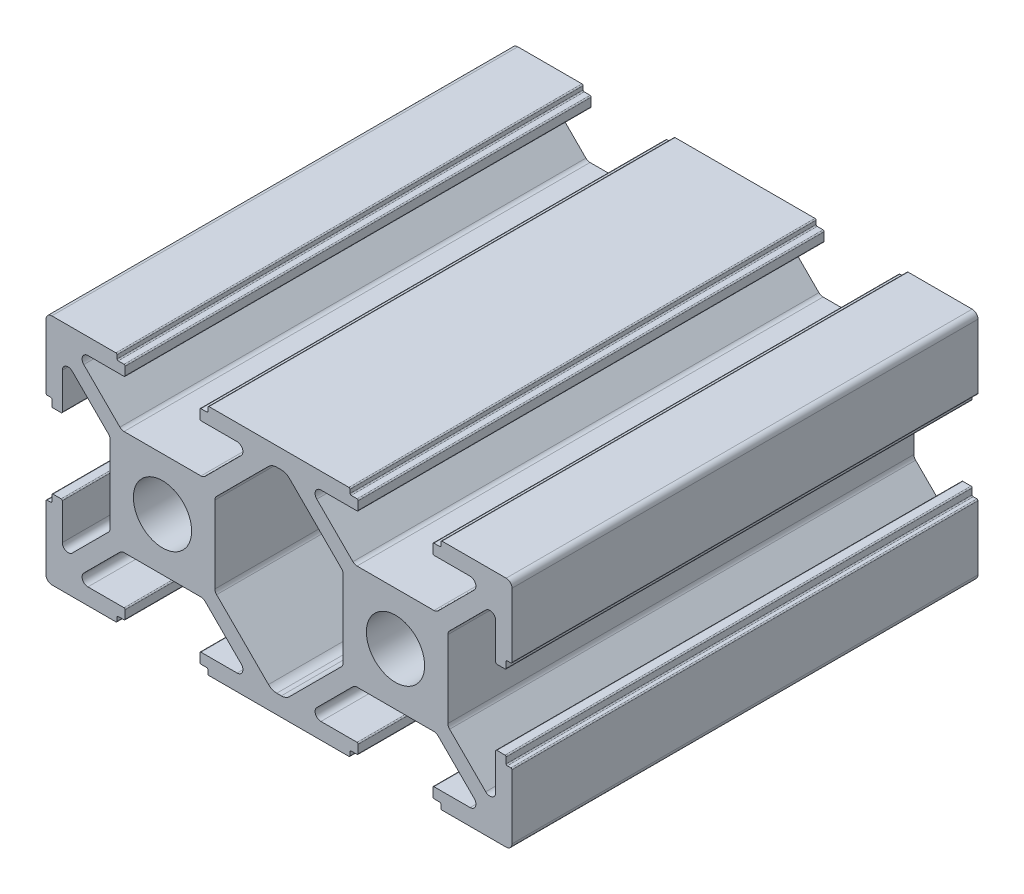
SolidWorks part; units mm, degrees
material "6061 Alaşım"
ref_plane "Ön Düzlem" through (0, 0, 0) normal (0, 0, 1) x (1, 0, 0)
ref_plane "Üst Düzlem" through (0, 0, 0) normal (0, 1, 0) x (1, 0, 0)
ref_plane "Sağ Düzlem" through (0, 0, 0) normal (1, 0, 0) x (0, 0, -1)
sketch "Çizim1" plane through (0, 0, 0) normal (0, 0, 1) x (1, 0, 0)
  line L0 (0, 0) -> (10, 10)
  line L1 (10, -10) -> (-10, -10)
  line L2 (10, -10) -> (10, 10)
  line L3 (10, 10) -> (-10, 10)
  line L4 (-10, -10) -> (-10, 10)
  line L5 (0, 10) -> (0, -10)
  line L6 (10, 0) -> (-10, 0)
  line L7 (4.5, 3.5101) -> (10, 9.0101)
  line L8 (3.5101, 4.5) -> (9.0101, 10)
  line L9 (10, 3.2) -> (8.6, 3.2)
  line L10 (8.6, 3.3) -> (8.6, 6.4029)
  line L11 (6.4029, 8.6) -> (3.3, 8.6)
  line L12 (3.2, 8.6) -> (3.2, 10)
  line L13 (3.6565, 4.6464) -> (6.7565, 7.7464)
  line L14 (7.7464, 6.7565) -> (4.6464, 3.6565)
  line L15 (3.2, 10) -> (9.5, 10)
  line L16 (10, 9.5) -> (10, 3.2)
  line L17 (4.5, 3.3029) -> (4.5, 0)
  line L18 (3.3029, 4.5) -> (0, 4.5)
  line L19 (3.3, 9.5) -> (3.8, 9.5)
  line L20 (3.9, 9.6) -> (3.9, 9.9)
  line L21 (3.2, 9.4) -> (3.2, 8.7)
  line L22 (4, 10) -> (9.5, 10)
  line L23 (9.5, 3.3) -> (9.5, 3.8)
  line L24 (9.6, 3.9) -> (9.9, 3.9)
  line L25 (8.7, 3.2) -> (9.4, 3.2)
  line L26 (10, 4) -> (10, 9.5)
  line L27 (0, 0) -> (10, -10)
  line L28 (3.3029, -4.5) -> (0, -4.5)
  line L29 (6.7565, -7.7464) -> (3.6565, -4.6464)
  line L30 (3.3, -8.6) -> (6.4029, -8.6)
  line L31 (3.2, -8.7) -> (3.2, -9.4)
  line L32 (3.3, -9.5) -> (3.8, -9.5)
  line L33 (3.9, -9.6) -> (3.9, -9.9)
  line L34 (4, -10) -> (9.5, -10)
  line L35 (10, -4) -> (10, -9.5)
  line L36 (9.6, -3.9) -> (9.9, -3.9)
  line L37 (9.5, -3.3) -> (9.5, -3.8)
  line L38 (9.4, -3.2) -> (8.7, -3.2)
  line L39 (8.6, -6.4029) -> (8.6, -3.3)
  line L40 (4.6464, -3.6565) -> (7.7464, -6.7565)
  line L41 (4.5, -3.3029) -> (4.5, 0)
  line L42 (0, 0) -> (-10, -10)
  line L43 (-4.5, -3.3029) -> (-4.5, 0)
  line L44 (-7.7464, -6.7565) -> (-4.6464, -3.6565) construction
  line L45 (-4.6464, 3.6565) -> (-9.0971, 8.1071)
  line L46 (-9.8042, 8.4) -> (-10, 8.4)
  line L47 (-10, -8.4) -> (-9.8042, -8.4)
  line L48 (-9.0971, -8.1071) -> (-4.6464, -3.6565)
  line L49 (-10, -4) -> (-10, -9.5)
  line L50 (-4, -10) -> (-9.5, -10)
  line L51 (-3.9, -9.6) -> (-3.9, -9.9)
  line L52 (-3.3, -9.5) -> (-3.8, -9.5)
  line L53 (-3.2, -9.4) -> (-3.2, -8.7)
  line L54 (-6.4029, -8.6) -> (-3.3, -8.6)
  line L55 (-3.6565, -4.6464) -> (-6.7565, -7.7464)
  line L56 (-3.3029, -4.5) -> (0, -4.5)
  line L57 (0, 0) -> (-10, 10)
  line L58 (-3.3029, 4.5) -> (0, 4.5)
  line L59 (-6.7565, 7.7464) -> (-3.6565, 4.6464)
  line L60 (-3.3, 8.6) -> (-6.4029, 8.6)
  line L61 (-3.2, 8.7) -> (-3.2, 9.4)
  line L62 (-3.3, 9.5) -> (-3.8, 9.5)
  line L63 (-3.9, 9.6) -> (-3.9, 9.9)
  line L64 (-4, 10) -> (-9.5, 10)
  line L65 (-10, 4) -> (-10, 9.5)
  line L70 (-4.6464, 3.6565) -> (-7.7464, 6.7565) construction
  line L71 (-4.5, 3.3029) -> (-4.5, 0)
  line L72 (-9.4, 3.2) -> (-8.7, 3.2) [skipped]
  line L73 (-8.6, 6.4029) -> (-8.6, 3.3) [skipped]
  line L74 (-9.5, 3.3) -> (-9.5, 3.8) [skipped]
  line L75 (-9.6, 3.9) -> (-9.9, 3.9) [skipped]
  line L76 (-8.6, -3.3) -> (-8.6, -6.4029) [skipped]
  line L77 (-9.6, -3.9) -> (-9.9, -3.9) [skipped]
  line L78 (-9.5, -3.3) -> (-9.5, -3.8) [skipped]
  line L79 (-8.7, -3.2) -> (-9.4, -3.2) [skipped]
  circle A0 centre (0, 0) radius 2.5
  arc A1 (10, 9.5) -> (9.5, 10) centre (9.5, 9.5) ccw
  arc A2 (4.5, 3.3029) -> (4.6464, 3.6565) centre (5, 3.3029) cw
  arc A3 (3.6565, 4.6464) -> (3.3029, 4.5) centre (3.3029, 5) cw
  arc A4 (8.6, 6.4029) -> (7.7464, 6.7565) centre (8.1, 6.4029) ccw
  arc A5 (6.4029, 8.6) -> (6.7565, 7.7464) centre (6.4029, 8.1) cw
  arc A6 (9.5, 3.8) -> (9.6, 3.9) centre (9.6, 3.8) cw
  arc A7 (9.9, 3.9) -> (10, 4) centre (9.9, 4) ccw
  arc A8 (8.7, 3.2) -> (8.6, 3.3) centre (8.7, 3.3) cw
  arc A9 (9.5, 3.3) -> (9.4, 3.2) centre (9.4, 3.3) cw
  arc A10 (3.3, 8.6) -> (3.2, 8.7) centre (3.3, 8.7) cw
  arc A11 (3.8, 9.5) -> (3.9, 9.6) centre (3.8, 9.6) ccw
  arc A12 (3.9, 9.9) -> (4, 10) centre (4, 9.9) cw
  arc A13 (3.3, 9.5) -> (3.2, 9.4) centre (3.3, 9.4) ccw
  arc A14 (3.3029, -4.5) -> (3.6565, -4.6464) centre (3.3029, -5) cw
  arc A15 (6.4029, -8.6) -> (6.7565, -7.7464) centre (6.4029, -8.1) ccw
  arc A16 (3.2, -8.7) -> (3.3, -8.6) centre (3.3, -8.7) cw
  arc A17 (3.3, -9.5) -> (3.2, -9.4) centre (3.3, -9.4) cw
  arc A18 (3.8, -9.5) -> (3.9, -9.6) centre (3.8, -9.6) cw
  arc A19 (3.9, -9.9) -> (4, -10) centre (4, -9.9) ccw
  arc A20 (9.5, -10) -> (10, -9.5) centre (9.5, -9.5) ccw
  arc A21 (9.9, -3.9) -> (10, -4) centre (9.9, -4) cw
  arc A22 (9.5, -3.8) -> (9.6, -3.9) centre (9.6, -3.8) ccw
  arc A23 (9.5, -3.3) -> (9.4, -3.2) centre (9.4, -3.3) ccw
  arc A24 (8.6, -3.3) -> (8.7, -3.2) centre (8.7, -3.3) cw
  arc A25 (8.6, -6.4029) -> (7.7464, -6.7565) centre (8.1, -6.4029) cw
  arc A26 (4.6464, -3.6565) -> (4.5, -3.3029) centre (5, -3.3029) cw
  arc A27 (-4.5, -3.3029) -> (-4.6464, -3.6565) centre (-5, -3.3029) cw
  arc A28 (-9.0971, 8.1071) -> (-9.8042, 8.4) centre (-9.8042, 7.4) ccw
  arc A29 (-9.8042, -8.4) -> (-9.0971, -8.1071) centre (-9.8042, -7.4) ccw
  arc A34 (-3.9, -9.9) -> (-4, -10) centre (-4, -9.9) cw
  arc A35 (-3.8, -9.5) -> (-3.9, -9.6) centre (-3.8, -9.6) ccw
  arc A36 (-3.3, -9.5) -> (-3.2, -9.4) centre (-3.3, -9.4) ccw
  arc A37 (-3.3, -8.6) -> (-3.2, -8.7) centre (-3.3, -8.7) cw
  arc A38 (-6.4029, -8.6) -> (-6.7565, -7.7464) centre (-6.4029, -8.1) cw
  arc A39 (-3.6565, -4.6464) -> (-3.3029, -4.5) centre (-3.3029, -5) cw
  arc A40 (-3.3029, 4.5) -> (-3.6565, 4.6464) centre (-3.3029, 5) cw
  arc A41 (-6.4029, 8.6) -> (-6.7565, 7.7464) centre (-6.4029, 8.1) ccw
  arc A42 (-3.2, 8.7) -> (-3.3, 8.6) centre (-3.3, 8.7) cw
  arc A43 (-3.3, 9.5) -> (-3.2, 9.4) centre (-3.3, 9.4) cw
  arc A44 (-3.8, 9.5) -> (-3.9, 9.6) centre (-3.8, 9.6) cw
  arc A45 (-3.9, 9.9) -> (-4, 10) centre (-4, 9.9) ccw
  arc A52 (-4.6464, 3.6565) -> (-4.5, 3.3029) centre (-5, 3.3029) cw
  arc A53 (-10, -9.5) -> (-9.5, -10) centre (-9.5, -9.5) ccw construction
  arc A54 (-9.5, 10) -> (-10, 9.5) centre (-9.5, 9.5) ccw construction
  arc A55 (-8.6, 3.3) -> (-8.7, 3.2) centre (-8.7, 3.3) cw [skipped]
  arc A56 (-9.5, 3.8) -> (-9.6, 3.9) centre (-9.6, 3.8) ccw [skipped]
  arc A57 (-9.9, 3.9) -> (-10, 4) centre (-9.9, 4) cw [skipped]
  arc A58 (-9.5, 3.3) -> (-9.4, 3.2) centre (-9.4, 3.3) ccw [skipped]
  arc A59 (-8.6, -6.4029) -> (-7.7464, -6.7565) centre (-8.1, -6.4029) ccw [skipped]
  arc A60 (-9.9, -3.9) -> (-10, -4) centre (-9.9, -4) ccw [skipped]
  arc A61 (-9.5, -3.8) -> (-9.6, -3.9) centre (-9.6, -3.8) cw [skipped]
  arc A62 (-9.5, -3.3) -> (-9.4, -3.2) centre (-9.4, -3.3) cw [skipped]
  arc A63 (-8.7, -3.2) -> (-8.6, -3.3) centre (-8.7, -3.3) cw [skipped]
  arc A64 (-8.6, 6.4029) -> (-7.7464, 6.7565) centre (-8.1, 6.4029) cw [skipped]
  point P0 (0, 0)
  point P32 (8.6, 7.6101)
  point P35 (7.6101, 8.6)
  point P41 (9.5, 3.9)
  point P44 (10, 3.9)
  point P50 (9.5, 3.2)
  point P62 (3.9, 9.5)
  point P65 (3.9, 10)
  point P68 (3.2, 9.5)
  point P198 (0, 0)
  dimension "D3" = 5
  dimension "D10" = 0.5
  dimension "D13" = 0.1
  dimension "D17" = 1
  dimension "D1" = 20
  dimension "D2" = 20
  dimension "D4" = 0.7
  dimension "D5" = 3.2
  dimension "D6" = 1.4
  dimension "D7" = 3.2
  dimension "D8" = 1.4
  dimension "D9" = 5.5
  dimension "D11" = 0.7
  dimension "D12" = 0.7
  dimension "D15" = 1.6
  dimension "D16" = 1.6
  dimension "D14" = 4
extrude "Yükseklik-Ekstrüzyon1" add sketch "Çizim1" against normal blind 40
mirror "Aynalama1"
